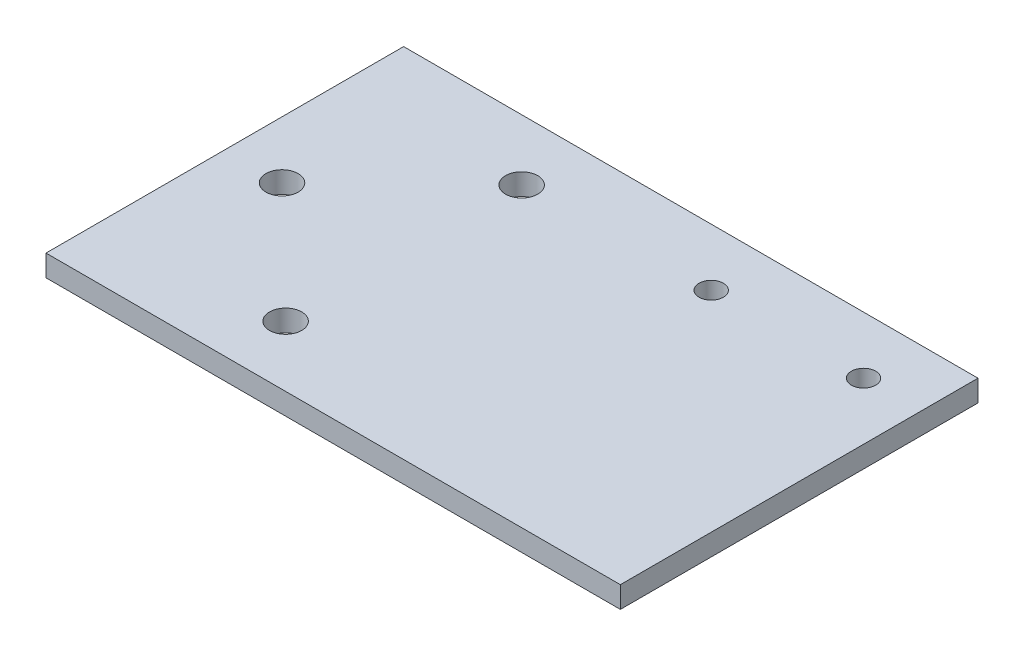
SolidWorks part; units mm, degrees
ref_plane "Front Plane" through (0, 0, 0) normal (0, 0, 1) x (1, 0, 0)
ref_plane "Top Plane" through (0, 0, 0) normal (0, 1, 0) x (1, 0, 0)
ref_plane "Right Plane" through (0, 0, 0) normal (1, 0, 0) x (0, 0, -1)
sketch "Sketch1" plane through (0, 0, 0) normal (0, 1, 0) x (1, 0, 0)
  line L0 (25, 41.5) -> (25, 8.5) construction
  line L1 (0, 0) -> (80.3, 0)
  line L2 (0, 0) -> (0, 50)
  line L3 (0, 50) -> (80.3, 50)
  line L4 (80.3, 0) -> (80.3, 50)
  line L5 (72.3, 42) -> (51, 42) construction
  line L9 (25, 8.5) -> (8, 25) construction
  line L10 (8, 25) -> (25, 41.5) construction
  circle A0 centre (51, 42) radius 1.7
  circle A1 centre (72.3, 42) radius 1.7
  circle A2 centre (8, 25) radius 2.25
  circle A3 centre (25, 8.5) radius 2.25
  circle A4 centre (25, 41.5) radius 2.25
  point P5 (70.2255, 41.5)
  point P7 (0, 0)
  point P17 (0, 0)
  point P18 (0, 0)
  dimension "D2" = 3.4
  dimension "D7" = 4.5
  dimension "D1" = 21.3
  dimension "D3" = 8
  dimension "D4" = 50
  dimension "D5" = 33
  dimension "D6" = 17
  dimension "D8" = 8.5
  dimension "D9" = 8
  dimension "D10" = 8
  dimension "D11" = 26
extrude "Boss-Extrude1" add sketch "Sketch1" along normal blind 3
